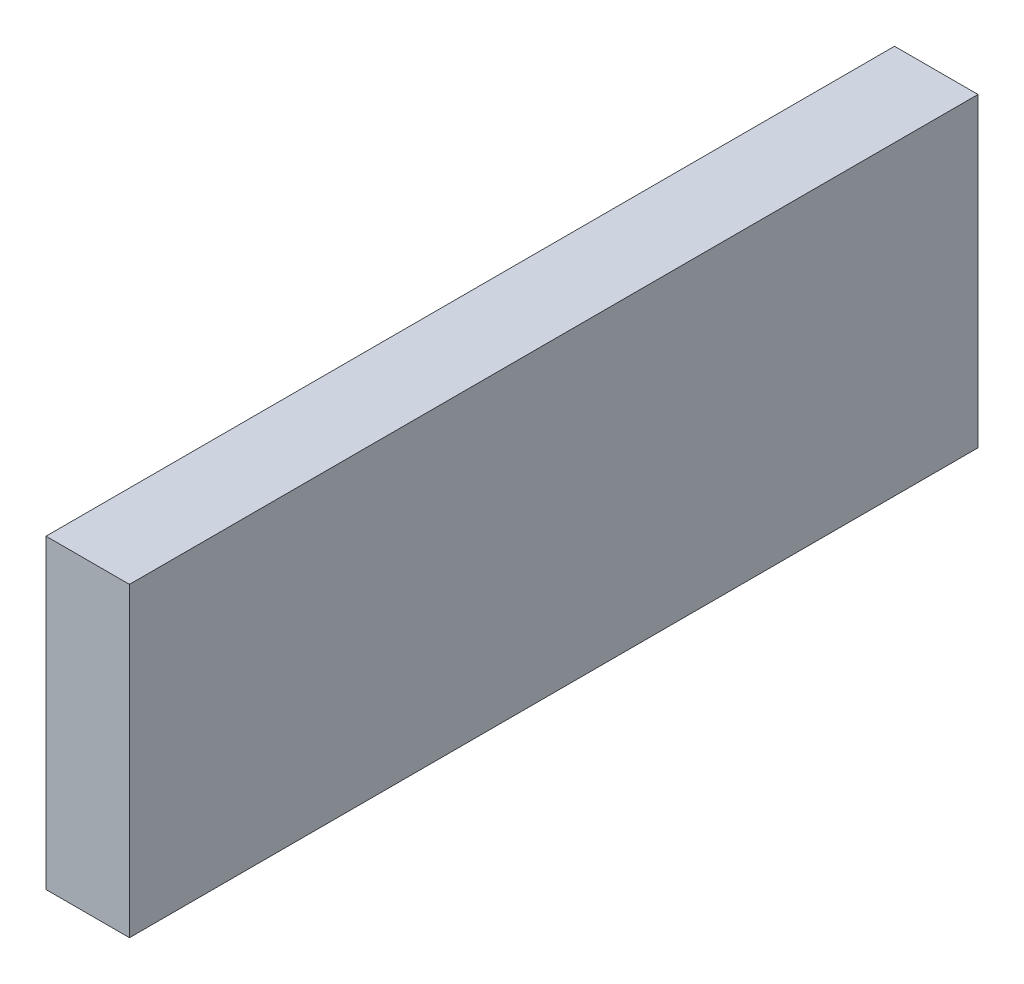
SolidWorks part; units mm, degrees
ref_plane "Front Plane" through (0, 0, 0) normal (0, 0, 1) x (1, 0, 0)
ref_plane "Top Plane" through (0, 0, 0) normal (0, 1, 0) x (1, 0, 0)
ref_plane "Right Plane" through (0, 0, 0) normal (1, 0, 0) x (0, 0, -1)
sketch "Sketch1" plane through (0, 0, 0) normal (0, 0, 1) x (1, 0, 0)
  line L1 (-19.05, -69.85) -> (19.05, -69.85)
  line L2 (-19.05, -69.85) -> (-19.05, 69.85)
  line L3 (-19.05, 69.85) -> (19.05, 69.85)
  line L4 (19.05, -69.85) -> (19.05, 69.85)
  line L5 (-19.05, -69.85) -> (19.05, 69.85) construction
  line L6 (-19.05, 69.85) -> (19.05, -69.85) construction
  point P0 (0, 0)
  dimension "D1" = 139.7
  dimension "D2" = 38.1
extrude "Boss-Extrude1" add sketch "Sketch1" along normal blind 387.35
equation "\"D1@Boss-Extrude1\"=96-78-2.75"
